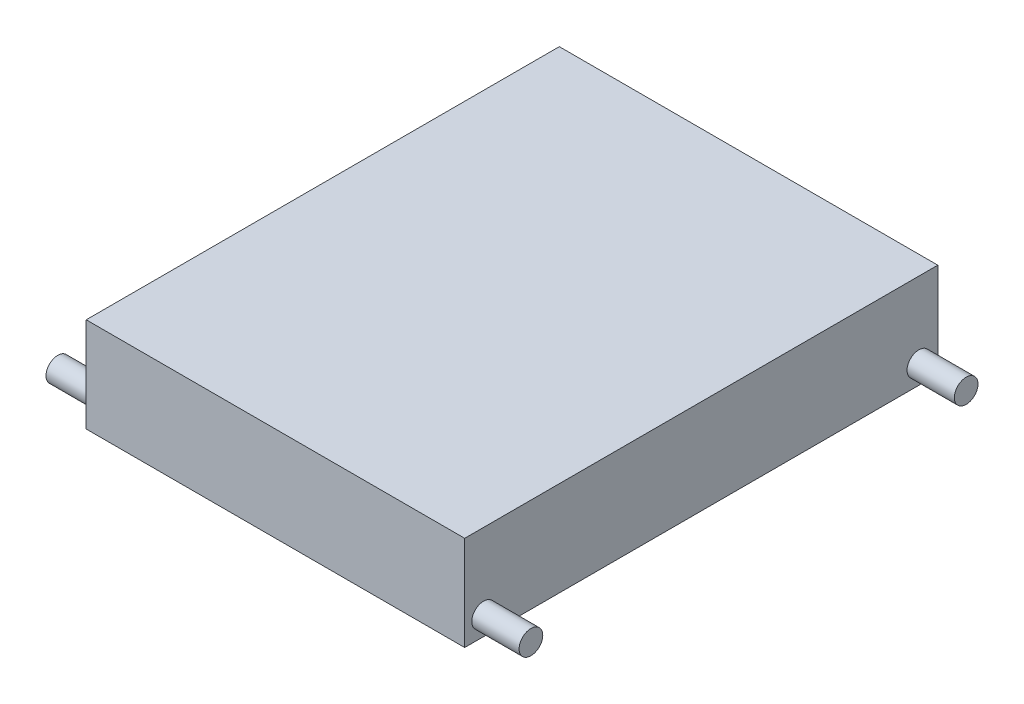
SolidWorks part; units mm, degrees
ref_plane "Front Plane" through (0, 0, 0) normal (0, 0, 1) x (1, 0, 0)
ref_plane "Top Plane" through (0, 0, 0) normal (0, 1, 0) x (1, 0, 0)
ref_plane "Right Plane" through (0, 0, 0) normal (1, 0, 0) x (0, 0, -1)
sketch "Sketch1" plane through (0, 0, 0) normal (0, 1, 0) x (1, 0, 0)
  line L1 (-38.1271, -18.3703) -> (63.4729, -18.3703)
  line L2 (-38.1271, -18.3703) -> (-38.1271, 108.6297)
  line L3 (-38.1271, 108.6297) -> (63.4729, 108.6297)
  line L4 (63.4729, -18.3703) -> (63.4729, 108.6297)
extrude "Boss-Extrude1" add sketch "Sketch1" along normal blind 25.4
sketch "Sketch2" plane through (63.4729, 0, 0) normal (1, 0, 0) x (0, 0, -1)
  line L0 (-18.3703, 0) -> (108.6297, 0) construction
  line L1 (-18.3703, 25.4) -> (-18.3703, 0) construction
  circle A0 centre (-13.2903, 5.08) radius 3.175
  dimension "D1" = 5.08
  dimension "D2" = 5.08
  dimension "D3" = 6.35
extrude "Boss-Extrude3" add sketch "Sketch2" along normal blind 12.7
sketch "Sketch3" plane through (63.4729, 0, 0) normal (1, 0, 0) x (0, 0, -1)
  line L0 (108.6297, 25.4) -> (108.6297, 0) construction
  line L1 (-18.3703, 0) -> (108.6297, 0) construction
  circle A0 centre (103.5497, 5.08) radius 3.175
  dimension "D1" = 6.35
  dimension "D2" = 5.08
  dimension "D3" = 5.08
extrude "Boss-Extrude4" add sketch "Sketch3" along normal blind 12.7
sketch "Sketch4" plane through (-38.1271, 0, 0) normal (-1, 0, 0) x (0, 0, 1)
  line L0 (-108.6297, 25.4) -> (-108.6297, 0) construction
  line L1 (-108.6297, 0) -> (18.3703, 0) construction
  circle A0 centre (-103.5497, 5.08) radius 3.175
  dimension "D1" = 6.35
  dimension "D2" = 5.08
  dimension "D3" = 5.08
extrude "Boss-Extrude6" add sketch "Sketch4" along normal blind 12.7
sketch "Sketch5" plane through (-38.1271, 0, 0) normal (-1, 0, 0) x (0, 0, 1)
  line L0 (18.3703, 25.4) -> (18.3703, 0) construction
  line L1 (-108.6297, 0) -> (18.3703, 0) construction
  circle A0 centre (13.2903, 5.08) radius 3.175
  dimension "D1" = 6.35
  dimension "D2" = 5.08
  dimension "D3" = 5.08
extrude "Boss-Extrude7" add sketch "Sketch5" along normal blind 12.7
